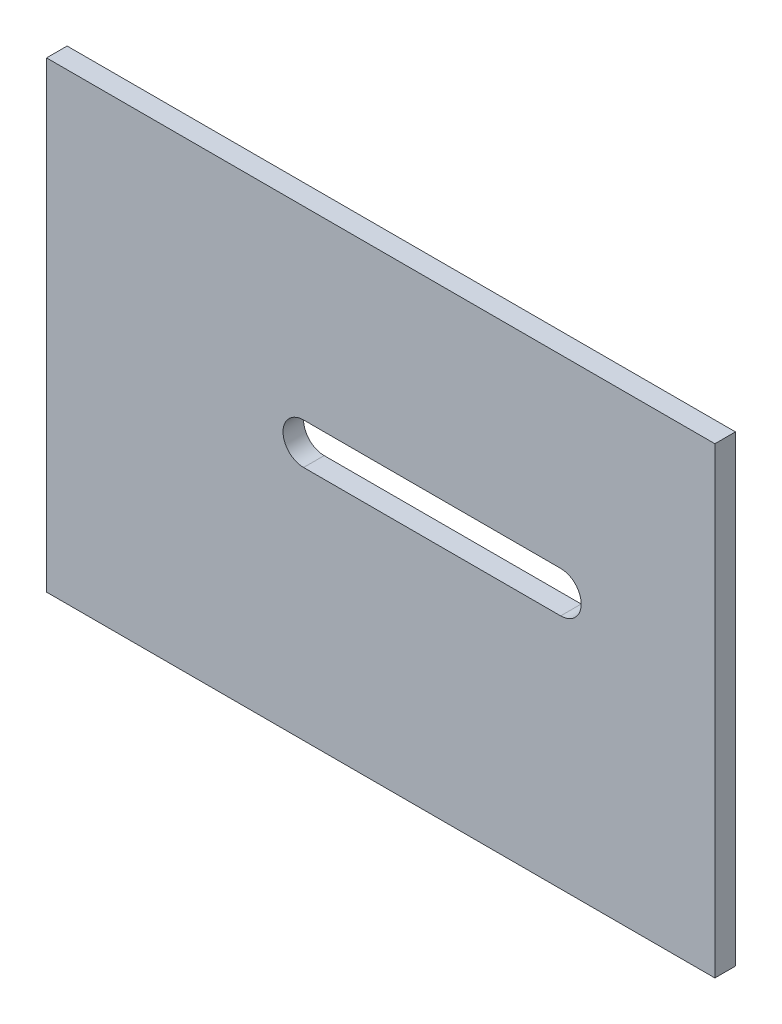
SolidWorks part; units mm, degrees
ref_plane "Front Plane" through (0, 0, 0) normal (0, 0, 1) x (1, 0, 0)
ref_plane "Top Plane" through (0, 0, 0) normal (0, 1, 0) x (1, 0, 0)
ref_plane "Right Plane" through (0, 0, 0) normal (1, 0, 0) x (0, 0, -1)
sketch "Sketch1" plane through (0, 0, 0) normal (0, 0, 1) x (1, 0, 0)
  line L1 (-32.5, 22.5) -> (32.5, 22.5)
  line L2 (-32.5, 22.5) -> (-32.5, -22.5)
  line L3 (-32.5, -22.5) -> (32.5, -22.5)
  line L4 (32.5, 22.5) -> (32.5, -22.5)
  line L5 (-32.5, 22.5) -> (32.5, -22.5) construction
  line L6 (-32.5, -22.5) -> (32.5, 22.5) construction
  point P0 (0, 0)
  dimension "D1" = 45
  dimension "D2" = 65
extrude "Boss-Extrude1" add sketch "Sketch1" along normal blind 2
sketch "Sketch2" plane through (0, 0, 0) normal (0, 0, 1) x (1, 0, 0)
  line L0 (-7.5, 2.5) -> (17.5, 2.5) construction
  line L1 (-7.5, 4.5) -> (17.5, 4.5)
  line L2 (-7.5, 0.5) -> (17.5, 0.5)
  line L3 (-32.5, -22.5) -> (32.5, -22.5) construction
  line L4 (32.5, -22.5) -> (32.5, 22.5) construction
  arc A0 (-7.5, 4.5) -> (-7.5, 0.5) centre (-7.5, 2.5) ccw
  arc A1 (17.5, 0.5) -> (17.5, 4.5) centre (17.5, 2.5) ccw
  point P2 (5, 2.5)
  dimension "D2" = 2
  dimension "D1" = 25
  dimension "D3" = 25
  dimension "D4" = 15
extrude "Cut-Extrude2" cut sketch "Sketch2" along normal blind 2
